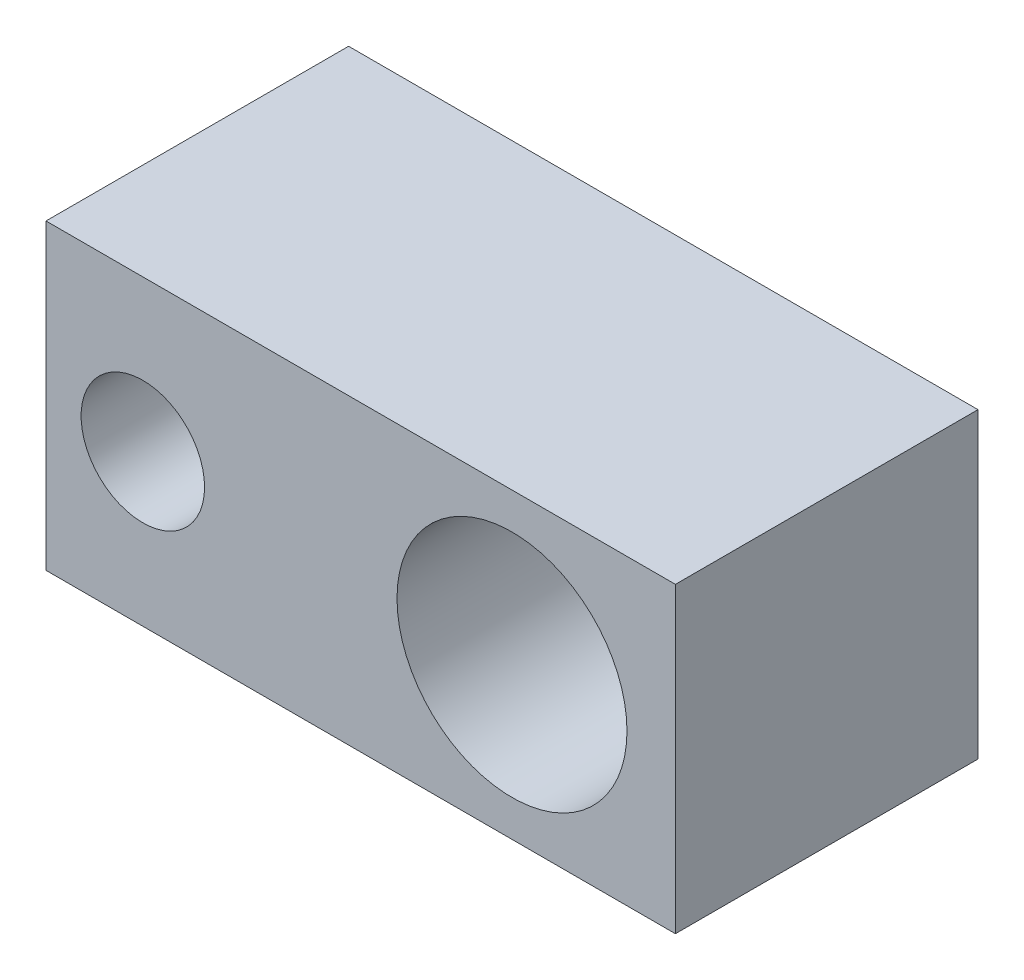
SolidWorks part; units mm, degrees
ref_plane "Front Plane" through (0, 0, 0) normal (0, 0, 1) x (1, 0, 0)
ref_plane "Top Plane" through (0, 0, 0) normal (0, 1, 0) x (1, 0, 0)
ref_plane "Right Plane" through (0, 0, 0) normal (1, 0, 0) x (0, 0, -1)
sketch "Sketch1" plane through (0, 0, 0) normal (0, 0, 1) x (1, 0, 0)
  line L1 (-26, -12.5) -> (26, -12.5)
  line L2 (-26, -12.5) -> (-26, 12.5)
  line L3 (-26, 12.5) -> (26, 12.5)
  line L4 (26, -12.5) -> (26, 12.5)
  line L5 (-26, -12.5) -> (26, 12.5) construction
  line L6 (-26, 12.5) -> (26, -12.5) construction
  circle A0 centre (12.5, 0) radius 9.5
  circle A1 centre (-18, 0) radius 5.1
  point P0 (0, 0)
  point P10 (0, 0)
  point P11 (0, 0)
  point P12 (-17.8361, -0.15)
  point P13 (0, 0)
  point P16 (-17.9462, 6.1262)
  dimension "D2" = 10.2
  dimension "D3" = 19
  dimension "D5" = 8
  dimension "D7" = 12.5
  dimension "D1" = 30.5
  dimension "D4" = 52
  dimension "D6" = 25
  dimension "D8" = 0
extrude "Boss-Extrude1" add sketch "Sketch1" along normal blind 25
